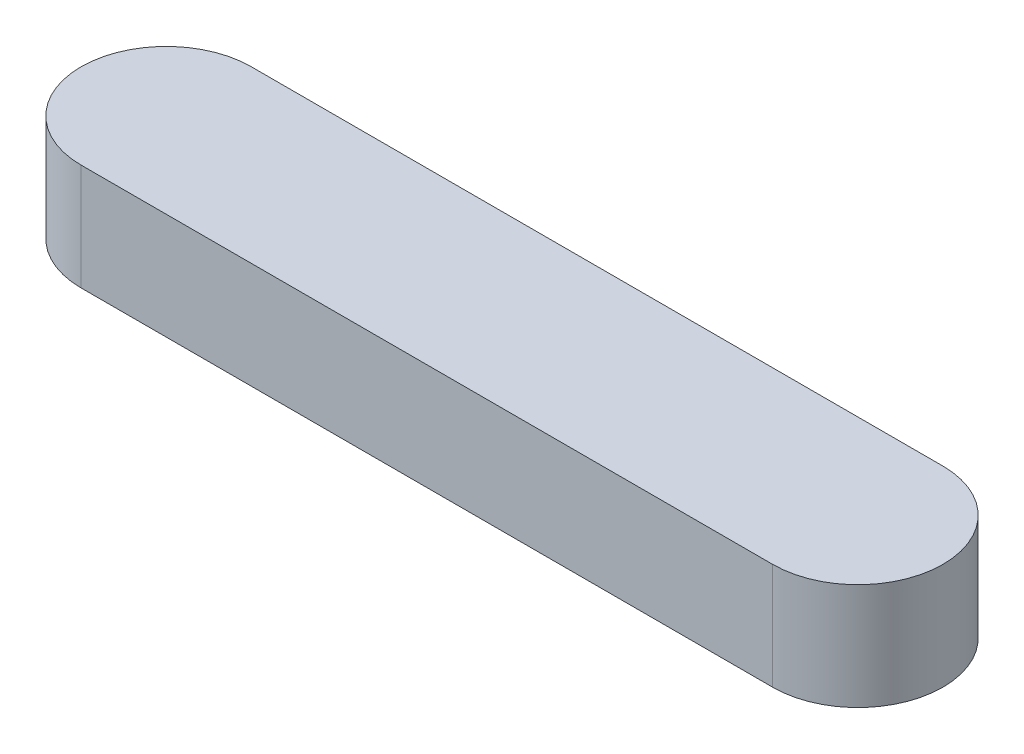
SolidWorks part; units mm, degrees
ref_plane "Front" through (0, 0, 0) normal (0, 0, 1) x (1, 0, 0)
ref_plane "Top" through (0, 0, 0) normal (0, 1, 0) x (1, 0, 0)
ref_plane "Right" through (0, 0, 0) normal (1, 0, 0) x (0, 0, -1)
sketch "Esquisse1" plane through (0, 0, 0) normal (0, 1, 0) x (1, 0, 0)
  line L0 (-32.5, 0) -> (32.5, 0) construction
  line L1 (-32.5, 8) -> (32.5, 8)
  line L2 (-32.5, -8) -> (32.5, -8)
  arc A0 (-32.5, 8) -> (-32.5, -8) centre (-32.5, 0) ccw
  arc A1 (32.5, -8) -> (32.5, 8) centre (32.5, 0) ccw
  point P2 (0, 0)
  dimension "D1" = 65
  dimension "D2" = 16
extrude "Boss.-Extru.1" add sketch "Esquisse1" along normal blind 10
